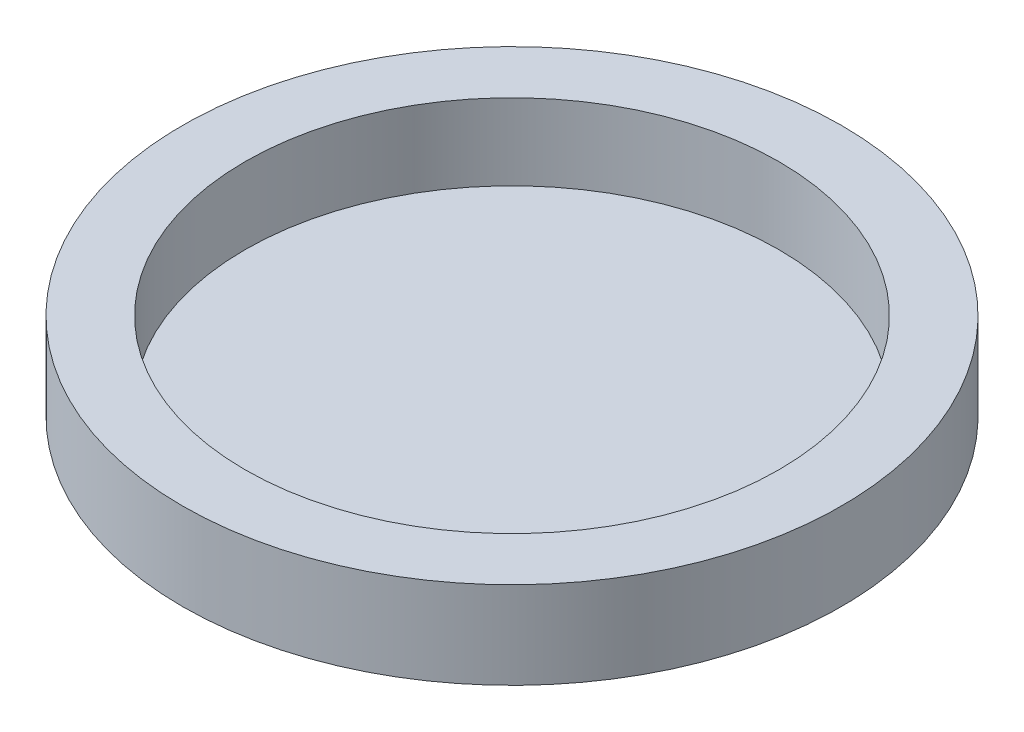
SolidWorks part; units mm, degrees
ref_plane "Front Plane" through (0, 0, 0) normal (0, 0, 1) x (1, 0, 0)
ref_plane "Top Plane" through (0, 0, 0) normal (0, 1, 0) x (1, 0, 0)
ref_plane "Right Plane" through (0, 0, 0) normal (1, 0, 0) x (0, 0, -1)
sketch "Sketch1" plane through (0, 0, 0) normal (0, 1, 0) x (1, 0, 0)
  circle A0 centre (0, 0) radius 30.25
  dimension "D1" = 60.5
extrude "Boss-Extrude1" add sketch "Sketch1" along normal blind 8 contours A0
sketch "Sketch2" plane through (0, 8, 0) normal (0, 1, 0) x (1, 0, 0)
  circle A0 centre (0, 0) radius 24.5
extrude "Cut-Extrude7" cut sketch "Sketch2" against normal blind 7 contours A0
